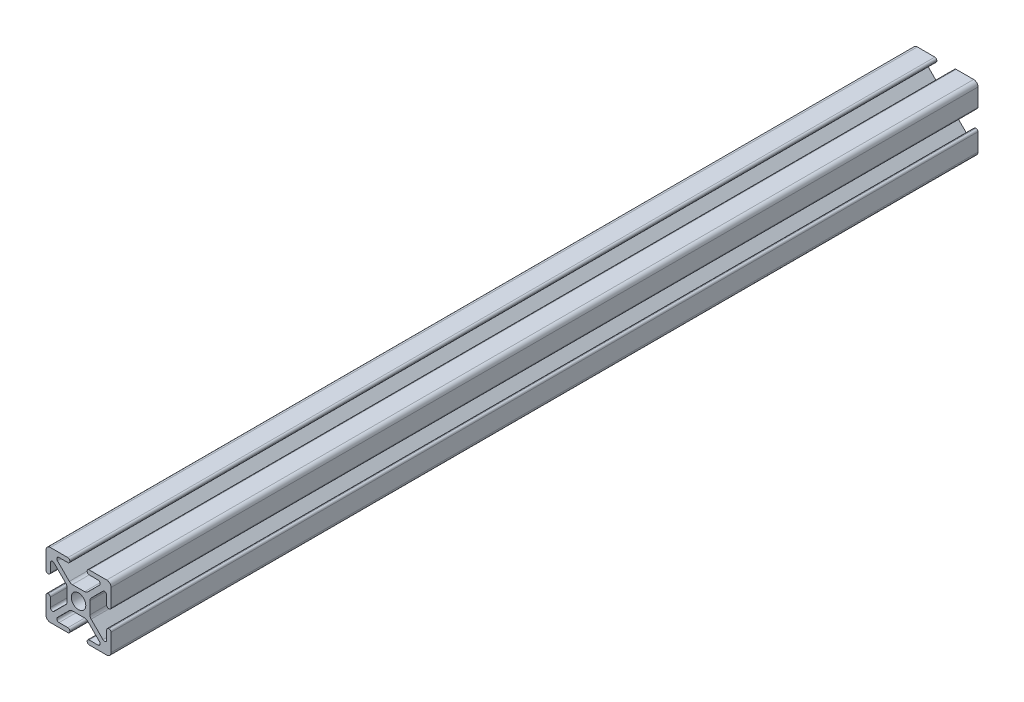
SolidWorks part; units mm, degrees
ref_plane "前视基准面" through (0, 0, 0) normal (0, 0, 1) x (1, 0, 0)
ref_plane "上视基准面" through (0, 0, 0) normal (0, 1, 0) x (1, 0, 0)
ref_plane "右视基准面" through (0, 0, 0) normal (1, 0, 0) x (0, 0, -1)
sketch "草图1" plane through (0, 0, 0) normal (0, 0, 1) x (1, 0, 0)
  line L0 (14.1, -4) -> (13.9, -4)
  line L1 (11.2929, -9.6929) -> (5.8358, -4.2358)
  line L2 (5.25, -2.8216) -> (5.25, 2.8216)
  line L3 (5.8358, 4.2358) -> (11.2929, 9.6929)
  line L4 (9.6929, 11.2929) -> (4.2358, 5.8358)
  line L5 (2.8216, 5.25) -> (-2.8216, 5.25)
  line L6 (-4.2358, 5.8358) -> (-9.6929, 11.2929)
  line L7 (-11.2929, 9.6929) -> (-5.8358, 4.2358)
  line L8 (-5.25, 2.8216) -> (-5.25, -2.8216)
  line L9 (-5.8358, -4.2358) -> (-11.2929, -9.6929)
  line L10 (-9.6929, -11.2929) -> (-4.2358, -5.8358)
  line L11 (-2.8216, -5.25) -> (2.8216, -5.25)
  line L12 (4.2358, -5.8358) -> (9.6929, -11.2929)
  line L13 (8.9858, -13) -> (4.9, -13)
  line L14 (4, -13.9) -> (4, -14.1)
  line L15 (15, -4.9) -> (15, -13)
  line L16 (4.9, -15) -> (13, -15)
  line L17 (13, -8.9858) -> (13, -4.9)
  line L18 (14.1, 4) -> (13.9, 4)
  line L19 (8.9858, 13) -> (4.9, 13)
  line L20 (4, 13.9) -> (4, 14.1)
  line L21 (4.9, 15) -> (13, 15)
  line L22 (15, 4.9) -> (15, 13)
  line L23 (13, 8.9858) -> (13, 4.9)
  line L24 (-14.1, -4) -> (-13.9, -4)
  line L25 (-8.9858, -13) -> (-4.9, -13)
  line L26 (-4, -13.9) -> (-4, -14.1)
  line L27 (-4.9, -15) -> (-13, -15)
  line L28 (-15, -4.9) -> (-15, -13)
  line L29 (-13, -8.9858) -> (-13, -4.9)
  line L30 (-14.1, 4) -> (-13.9, 4)
  line L31 (-8.9858, 13) -> (-4.9, 13)
  line L32 (-4, 13.9) -> (-4, 14.1)
  line L33 (-4.9, 15) -> (-13, 15)
  line L34 (-15, 4.9) -> (-15, 13)
  line L35 (-13, 8.9858) -> (-13, 4.9)
  circle A0 centre (0, 0) radius 3.35
  arc A1 (11.2929, -9.6929) -> (13, -8.9858) centre (12, -8.9858) ccw
  arc A2 (5.25, -2.8216) -> (5.8358, -4.2358) centre (7.25, -2.8216) ccw
  arc A3 (5.8358, 4.2358) -> (5.25, 2.8216) centre (7.25, 2.8216) ccw
  arc A4 (13, 8.9858) -> (11.2929, 9.6929) centre (12, 8.9858) ccw
  arc A5 (9.6929, 11.2929) -> (8.9858, 13) centre (8.9858, 12) ccw
  arc A6 (2.8216, 5.25) -> (4.2358, 5.8358) centre (2.8216, 7.25) ccw
  arc A7 (-4.2358, 5.8358) -> (-2.8216, 5.25) centre (-2.8216, 7.25) ccw
  arc A8 (-8.9858, 13) -> (-9.6929, 11.2929) centre (-8.9858, 12) ccw
  arc A9 (-11.2929, 9.6929) -> (-13, 8.9858) centre (-12, 8.9858) ccw
  arc A10 (-5.25, 2.8216) -> (-5.8358, 4.2358) centre (-7.25, 2.8216) ccw
  arc A11 (-5.8358, -4.2358) -> (-5.25, -2.8216) centre (-7.25, -2.8216) ccw
  arc A12 (-13, -8.9858) -> (-11.2929, -9.6929) centre (-12, -8.9858) ccw
  arc A13 (-9.6929, -11.2929) -> (-8.9858, -13) centre (-8.9858, -12) ccw
  arc A14 (-2.8216, -5.25) -> (-4.2358, -5.8358) centre (-2.8216, -7.25) ccw
  arc A15 (4.2358, -5.8358) -> (2.8216, -5.25) centre (2.8216, -7.25) ccw
  arc A16 (8.9858, -13) -> (9.6929, -11.2929) centre (8.9858, -12) ccw
  arc A17 (13.9, -4) -> (13, -4.9) centre (13.9, -4.9) ccw
  arc A18 (15, -4.9) -> (14.1, -4) centre (14.1, -4.9) ccw
  arc A19 (4.9, -13) -> (4, -13.9) centre (4.9, -13.9) ccw
  arc A20 (4, -14.1) -> (4.9, -15) centre (4.9, -14.1) ccw
  arc A21 (13, -15) -> (15, -13) centre (13, -13) ccw
  arc A22 (13, 4.9) -> (13.9, 4) centre (13.9, 4.9) ccw
  arc A23 (4, 13.9) -> (4.9, 13) centre (4.9, 13.9) ccw
  arc A24 (4.9, 15) -> (4, 14.1) centre (4.9, 14.1) ccw
  arc A25 (15, 13) -> (13, 15) centre (13, 13) ccw
  arc A26 (14.1, 4) -> (15, 4.9) centre (14.1, 4.9) ccw
  arc A27 (-13, -4.9) -> (-13.9, -4) centre (-13.9, -4.9) ccw
  arc A28 (-4, -13.9) -> (-4.9, -13) centre (-4.9, -13.9) ccw
  arc A29 (-4.9, -15) -> (-4, -14.1) centre (-4.9, -14.1) ccw
  arc A30 (-15, -13) -> (-13, -15) centre (-13, -13) ccw
  arc A31 (-14.1, -4) -> (-15, -4.9) centre (-14.1, -4.9) ccw
  arc A32 (-13.9, 4) -> (-13, 4.9) centre (-13.9, 4.9) ccw
  arc A33 (-4.9, 13) -> (-4, 13.9) centre (-4.9, 13.9) ccw
  arc A34 (-4, 14.1) -> (-4.9, 15) centre (-4.9, 14.1) ccw
  arc A35 (-13, 15) -> (-15, 13) centre (-13, 13) ccw
  arc A36 (-15, 4.9) -> (-14.1, 4) centre (-14.1, 4.9) ccw
  point P0 (0, 0.001)
  point P1 (0.001, 0.001)
  point P2 (0.001, 0)
extrude "凸台-拉伸1" add sketch "草图1" along normal blind 400
sketch "Sketch1" plane through (5.25, 0, 0) normal (1, 0, 0) x (0, 0, -1)
  line L0 (0, 0) -> (-2206.6738, 0) construction
  line L1 (-1040.5, 103.8298) -> (-1040.5, -185.7534) construction
  circle A0 centre (-1040.5, 0) radius 3
  circle A1 centre (-15, 0) radius 3
  circle A2 centre (-2066, 0) radius 3
  dimension "D2" = 15
  dimension "D3" = 6
  dimension "D4" = 6
  dimension "D1" = 1040.5
extrude "Cut-Extrude1" [suppressed] cut sketch "Sketch1" against normal blind 300
